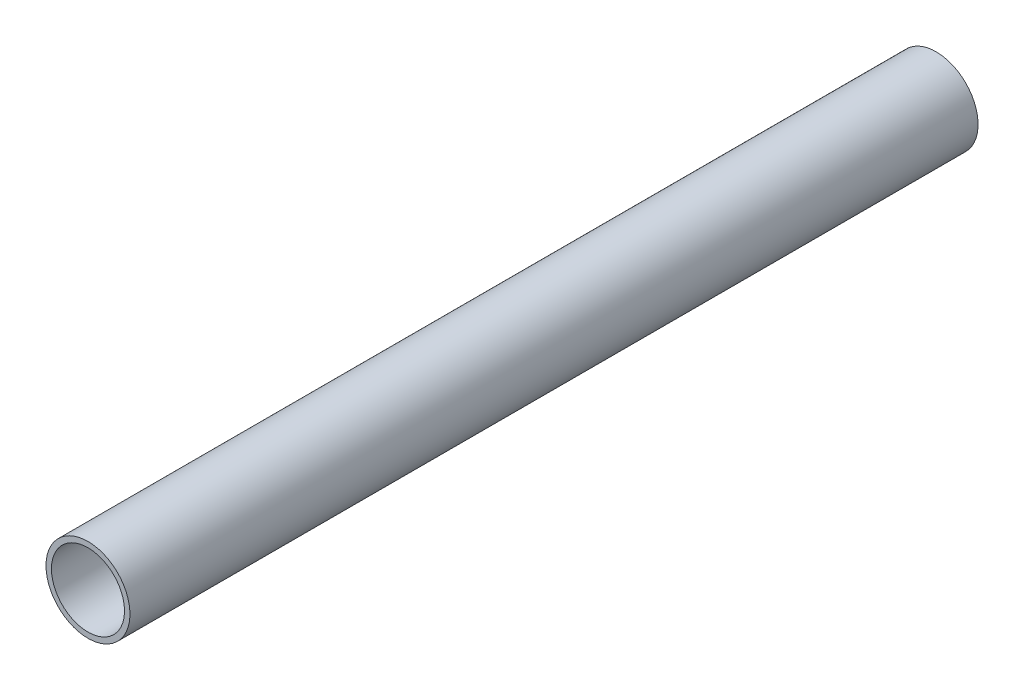
SolidWorks part; units mm, degrees
other "Published References"
other "Connector1"
other "Connector2"
ref_plane "Front Plane" through (0, 0, 0) normal (0, 0, 1) x (1, 0, 0)
ref_plane "Top Plane" through (0, 0, 0) normal (0, 1, 0) x (1, 0, 0)
ref_plane "Right Plane" through (0, 0, 0) normal (1, 0, 0) x (0, 0, -1)
sketch "Sketch1" plane through (0, 0, 0) normal (0, 0, 1) x (1, 0, 0)
  circle A0 centre (0, 0) radius 30.1625
  circle A1 centre (0, 0) radius 26.2509
  dimension "D1" = 52.5018
  dimension "D2" = 60.325
extrude "Boss-Extrude1" add sketch "Sketch1" along normal blind 609.6
